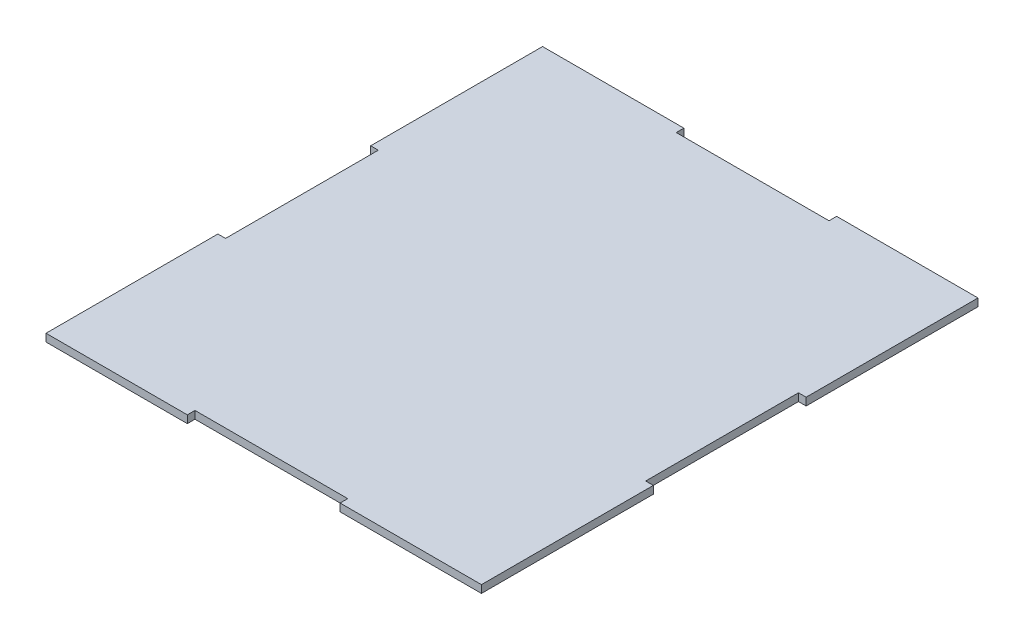
SolidWorks part; units mm, degrees
ref_plane "Ebene vorne" through (0, 0, 0) normal (0, 0, 1) x (1, 0, 0)
ref_plane "Ebene oben" through (0, 0, 0) normal (0, 1, 0) x (1, 0, 0)
ref_plane "Ebene rechts" through (0, 0, 0) normal (1, 0, 0) x (0, 0, -1)
sketch "Skizze1" plane through (0, 0, 0) normal (0, 1, 0) x (1, 0, 0)
  line L1 (0, 0) -> (285, 0)
  line L2 (0, 0) -> (0, 325)
  line L3 (0, 325) -> (285, 325)
  line L4 (285, 0) -> (285, 325)
  dimension "D1" = 285
  dimension "D2" = 325
extrude "Aufsatz-Linear austragen1" add sketch "Skizze1" along normal blind 5
sketch "Skizze2" plane through (0, 5, 0) normal (0, 1, 0) x (1, 0, 0)
  line L0 (142.5, 325) -> (142.5, 162.5) construction
  line L1 (285, 325) -> (0, 325) construction
  line L2 (142.5, 162.5) -> (0, 162.5) construction
  line L3 (0, 325) -> (0, 0) construction
  line L4 (142.5, 325) -> (92.5, 325)
  line L5 (92.5, 325) -> (92.5, 320)
  line L6 (92.5, 320) -> (192.5, 320)
  line L7 (0, 112.5) -> (0, 212.5)
  line L8 (0, 212.5) -> (5, 212.5)
  line L9 (5, 212.5) -> (5, 112.5)
  line L10 (192.5, 325) -> (192.5, 320)
  line L11 (142.5, 325) -> (192.5, 325)
  line L12 (0, 112.5) -> (5, 112.5)
  line L13 (285, 112.5) -> (280, 112.5)
  line L14 (280, 212.5) -> (280, 112.5)
  line L15 (285, 212.5) -> (280, 212.5)
  line L16 (285, 112.5) -> (285, 212.5)
  line L17 (142.5, 0) -> (192.5, 0)
  line L18 (192.5, 0) -> (192.5, 5)
  line L19 (92.5, 5) -> (192.5, 5)
  line L20 (92.5, 0) -> (92.5, 5)
  line L21 (142.5, 0) -> (92.5, 0)
  point P15 (142.5, 320)
  point P18 (5, 162.5)
  point P23 (280, 162.5)
  point P30 (142.5, 5)
  point P31 (142.1734, 325)
  dimension "D1" = 100
  dimension "D2" = 5
extrude "Schnitt-Linear austragen1" cut sketch "Skizze2" against normal through all
